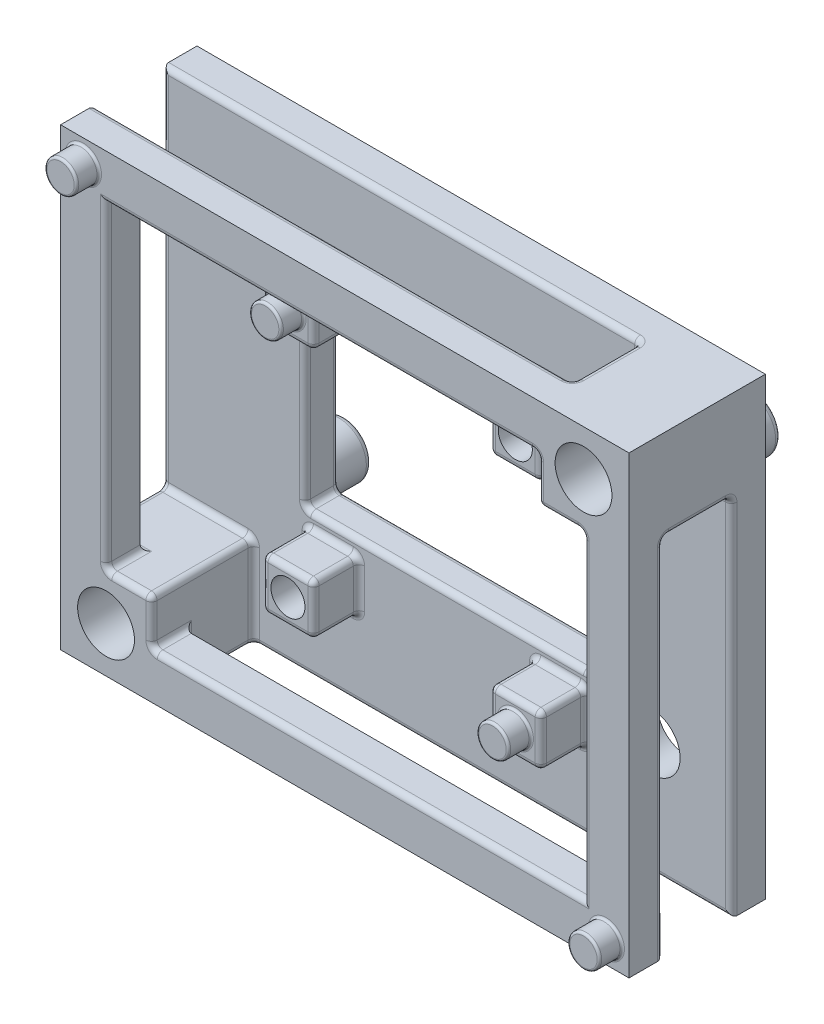
SolidWorks part; units mm, degrees
ref_plane "Ebene vorne" through (0, 0, 0) normal (0, 0, 1) x (1, 0, 0)
ref_plane "Ebene oben" through (0, 0, 0) normal (0, 1, 0) x (1, 0, 0)
ref_plane "Ebene rechts" through (0, 0, 0) normal (1, 0, 0) x (0, 0, -1)
sketch "Sketch1" plane through (0, 0, 0) normal (0, 0, 1) x (1, 0, 0)
  line L1 (-25, -20) -> (25, -20)
  line L2 (-25, -20) -> (-25, 20)
  line L3 (-25, 20) -> (25, 20)
  line L4 (25, -20) -> (25, 20)
  line L5 (-25, -20) -> (25, 20) construction
  line L6 (-25, 20) -> (25, -20) construction
  point P0 (0, 0)
  dimension "D1" = 50
  dimension "D2" = 40
extrude "Boss-Extrude1" add sketch "Sketch1" along normal blind 3 contours L2 L1 L4 L3
sketch "Sketch2" plane through (0, 0, 0) normal (0, 0, 1) x (1, 0, 0)
  line L2 (0, 0) -> (5.3997, -5.3997) construction
  circle A0 centre (18, 10) radius 2.4
  circle A2 centre (-18, -10) radius 2.4
  circle A4 centre (-18, -10) radius 2.4
  dimension "D3" = 4.8
  dimension "D6" = 4.8
  dimension "D1" = 18
  dimension "D2" = 10
  dimension "D4" = 18
  dimension "D5" = 10
extrude "Boss-Extrude2" add sketch "Sketch2" against normal blind 7 from offset 1 contours A0 | A2
sketch "Sketch3" plane through (0, 0, 0) normal (0, 0, 1) x (1, 0, 0)
  line L1 (-12, -7.5) -> (12, -7.5)
  line L2 (-12.5, -7) -> (-12.5, 7)
  line L3 (-12, 7.5) -> (12, 7.5)
  line L4 (12.5, -7) -> (12.5, 7)
  line L5 (-12.5, -7.5) -> (12.5, 7.5) construction
  line L6 (-12.5, 7.5) -> (12.5, -7.5) construction
  circle A0 centre (18, -10) radius 2.5
  circle A2 centre (-18, 10) radius 2.5
  circle A4 centre (-18, 10) radius 2.5
  arc A5 (-12.5, 7) -> (-12, 7.5) centre (-12, 7) cw
  arc A6 (12, -7.5) -> (12.5, -7) centre (12, -7) ccw
  arc A7 (-12, -7.5) -> (-12.5, -7) centre (-12, -7) cw
  arc A8 (12, 7.5) -> (12.5, 7) centre (12, 7) cw
  point P2 (0, 0)
  dimension "D3" = 5
  dimension "D6" = 5
  dimension "D9" = 0.5
  dimension "D1" = 18
  dimension "D2" = 10
  dimension "D4" = 10
  dimension "D5" = 18
  dimension "D7" = 25
  dimension "D8" = 15
extrude "Cut-Extrude1" cut sketch "Sketch3" along normal blind 15 contours A2 | A0 | A7 L1 A6 L4 A8 L3 A5 L2
fillet "Fillet1" radius 0.5 2 edges at (20.4, 10, -6) (-15.6, -10, -6)
sketch "Sketch12" plane through (0, 0, 0) normal (0, 0, 1) x (1, 0, 0)
  line L0 (0, 0) -> (0, -6.125) construction
  line L1 (-12.25, 13.25) -> (-7.75, 13.25)
  line L2 (-12.25, 13.25) -> (-12.25, 8.75)
  line L3 (-12.25, 8.75) -> (-7.75, 8.75)
  line L4 (-7.75, 13.25) -> (-7.75, 8.75)
  line L5 (-12.25, 13.25) -> (-7.75, 8.75) construction
  line L6 (-12.25, 8.75) -> (-7.75, 13.25) construction
  line L7 (0, 0) -> (9.2744, 0) construction
  line L8 (-12.25, -8.75) -> (-7.75, -13.25) construction
  line L9 (-12.25, -13.25) -> (-7.75, -8.75) construction
  line L10 (-7.75, -13.25) -> (-7.75, -8.75)
  line L11 (-12.25, -8.75) -> (-7.75, -8.75)
  line L12 (-12.25, -13.25) -> (-12.25, -8.75)
  line L13 (-12.25, -13.25) -> (-7.75, -13.25)
  line L14 (12.25, -13.25) -> (7.75, -8.75) construction
  line L15 (12.25, -8.75) -> (7.75, -13.25) construction
  line L16 (12.25, 8.75) -> (7.75, 13.25) construction
  line L17 (12.25, 13.25) -> (7.75, 8.75) construction
  line L18 (12.25, -13.25) -> (7.75, -13.25)
  line L19 (12.25, -13.25) -> (12.25, -8.75)
  line L20 (12.25, -8.75) -> (7.75, -8.75)
  line L21 (7.75, -13.25) -> (7.75, -8.75)
  line L22 (7.75, 13.25) -> (7.75, 8.75)
  line L23 (12.25, 8.75) -> (7.75, 8.75)
  line L24 (12.25, 13.25) -> (12.25, 8.75)
  line L25 (12.25, 13.25) -> (7.75, 13.25)
  circle A0 centre (-10, 11) radius 1.5
  circle A1 centre (-10, -11) radius 1.5
  circle A2 centre (10, -11) radius 1.5
  circle A3 centre (10, 11) radius 1.5
  point P0 (-10, 11)
  dimension "D5" = 3
  dimension "D1" = 10
  dimension "D2" = 11
  dimension "D3" = 4.5
  dimension "D4" = 4.5
extrude "Boss-Extrude3" add sketch "Sketch12" along normal blind 7
sketch "Sketch13" plane through (0, 0, 0) normal (0, 0, 1) x (1, 0, 0)
  line L0 (0, 0) -> (-6.7923, 0) construction
  line L1 (17, 20) -> (25, 20)
  line L2 (17, 20) -> (17, 12)
  line L3 (17, 12) -> (25, 12)
  line L4 (25, 20) -> (25, 12)
  line L5 (17, 20) -> (25, 12) construction
  line L6 (17, 12) -> (25, 20) construction
  line L7 (0, 0) -> (0, 5.1433) construction
  line L9 (-25, -12) -> (-17, -12)
  line L10 (-25, -12) -> (-25, -20)
  line L11 (-25, -20) -> (-17, -20)
  line L12 (-17, -12) -> (-17, -20)
  line L13 (-25, -12) -> (-17, -20) construction
  line L14 (-25, -20) -> (-17, -12) construction
  circle A0 centre (21, 16) radius 2.5
  circle A1 centre (-21, -16) radius 2.5
  point P0 (21, 16)
  point P11 (-21, -16)
  dimension "D5" = 5
  dimension "D10" = 5
  dimension "D1" = 21
  dimension "D2" = 16
  dimension "D3" = 8
  dimension "D4" = 8
  dimension "D6" = 16
  dimension "D7" = 21
  dimension "D8" = 8
  dimension "D9" = 8
extrude "Boss-Extrude4" add sketch "Sketch13" along normal blind 12
sketch "Sketch14" plane through (0, 0, 0) normal (0, 0, 1) x (1, 0, 0)
  line L1 (-25, -20) -> (25, -20)
  line L2 (-25, -20) -> (-25, 20)
  line L3 (-25, 20) -> (25, 20)
  line L4 (25, -20) -> (25, 20)
  line L5 (-25, -20) -> (25, 20) construction
  line L6 (-25, 20) -> (25, -20) construction
  line L7 (-21, -16) -> (21, -16)
  line L8 (-21, -16) -> (-21, 16)
  line L9 (-21, 16) -> (21, 16)
  line L10 (21, -16) -> (21, 16)
  line L11 (-21, -16) -> (21, 16) construction
  line L12 (-21, 16) -> (21, -16) construction
  point P0 (0, 0)
  point P6 (0, 0)
  dimension "D1" = 40
  dimension "D2" = 50
  dimension "D3" = 32
  dimension "D4" = 42
extrude "Boss-Extrude5" add sketch "Sketch14" along normal blind 3 from offset 9
sketch "Sketch15" plane through (0, 0, 0) normal (0, 0, 1) x (1, 0, 0)
  circle A0 centre (-10, 11) radius 2
  circle A1 centre (10, -11) radius 2
  dimension "D1" = 4
  dimension "D2" = 4
extrude "Boss-Extrude6" add sketch "Sketch15" along normal blind 7
sketch "Sketch16" plane through (0, 0, 0) normal (0, 0, 1) x (1, 0, 0)
  circle A0 centre (-10, 11) radius 1.4
  circle A1 centre (10, -11) radius 1.4
  dimension "D3" = 2.8
  dimension "D4" = 2.8
  dimension "D1" = 11
  dimension "D2" = 10
  dimension "D5" = 11
  dimension "D6" = 10
extrude "Boss-Extrude7" add sketch "Sketch16" along normal blind 9
sketch "Sketch17" plane through (0, 0, 0) normal (0, 0, 1) x (1, 0, 0)
  circle A0 centre (-21, -16) radius 2.5
  circle A1 centre (21, 16) radius 2.5
  circle A2 centre (10, 11) radius 1.5
  circle A3 centre (-10, -11) radius 1.5
  dimension "D1" = 3
  dimension "D2" = 3
  dimension "D3" = 5
  dimension "D4" = 5
  dimension "D5" = 21
  dimension "D6" = 16
extrude "Cut-Extrude2" cut sketch "Sketch17" along normal blind 15 from offset 1 offset against normal yes
fillet "Fillet4" radius 0.5 50 edges at (-25, 4, 3) (-21, 2, 12) (-25, 4, 9) (2, -16, 12) (4, -20, 3) (4, -20, 9) (-2, 16, 12) (-4, 20, 3) (-4, 20, 9) (25, -4, 3) (21, -2, 12) (25, -4, 9) (-12.3536, 7.3536, 0) (-12.5, 0, 0) (-12.3536, -7.3536, 0) (0, -7.5, 0) (12.3536, -7.3536, 0) (12.5, 0, 0) (12.3536, 7.3536, 0) (12.3536, 7.3536, 3) (12.5, 0, 3) (12.3536, -7.3536, 3) (0, -7.5, 3) (-12.3536, -7.3536, 3) (-12.5, 0, 3) (-12.3536, 7.3536, 3) (-21, -12, 3) (-19, -12, 12) (-21, -12, 10.5) (-23, -12, 9) (-25, -12, 6) (-17, -14, 12) (-17, -12, 7.5) (-17, -16, 3) (-17, -20, 6) (-17, -18, 9) (-17, -16, 10.5) (17, 14, 12) (17, 16, 3) (17, 20, 6) (17, 18, 9) (17, 16, 10.5) (21, 12, 3) (17, 12, 7.5) (19, 12, 12) (21, 12, 10.5) (23, 12, 9) (25, 12, 6) (0, 7.5, 0) (0, 7.5, 3)
fillet "Fillet5" radius 0.5 48 edges at (-7.75, -11, 3) (-10, -8.75, 3) (-10, -13.25, 7) (-7.75, -13.25, 5) (-10, -13.25, 3) (-12.25, -8.75, 5) (-12.25, -11, 7) (-12.25, -13.25, 5) (-12.25, -11, 3) (-7.75, -8.75, 5) (12.25, 11, 7) (12.25, 11, 3) (12.25, -11, 3) (12.25, -11, 7) (12.25, -8.75, 5) (10, -8.75, 3) (10, -8.75, 7) (12.25, 13.25, 5) (10, 13.25, 7) (10, 13.25, 3) (7.75, -8.75, 5) (7.75, -11, 3) (7.75, -11, 7) (7.75, 13.25, 5) (7.75, 11, 7) (7.75, 11, 3) (7.75, -13.25, 5) (10, -13.25, 3) (10, -13.25, 7) (12.25, -13.25, 5) (7.75, 8.75, 5) (10, 8.75, 7) (12.25, 8.75, 5) (10, 8.75, 3) (-12.25, 11, 3) (-12.25, 11, 7) (-10, 13.25, 3) (-10, 13.25, 7) (-12.25, 13.25, 5) (-12.25, 8.75, 5) (-10, 8.75, 3) (-10, 8.75, 7) (-7.75, 8.75, 5) (-7.75, 11, 3) (-7.75, 11, 7) (-7.75, 13.25, 5) (-10, -8.75, 7) (-7.75, -11, 7)
fillet "Fillet6" radius 0.2 2 edges at (11.4, -11, 9) (-8.6, 11, 9)
fillet "Fillet7" radius 0.2 2 edges at (11.4, -11, 7) (-8.6, 11, 7)
sketch "Sketch18" plane through (0, 0, 0) normal (0, 0, 1) x (1, 0, 0)
  circle A0 centre (-23, 18) radius 1.4
  circle A1 centre (23, -18) radius 1.4
  dimension "D3" = 2.8
  dimension "D6" = 2.8
  dimension "D1" = 18
  dimension "D2" = 23
  dimension "D4" = 18
  dimension "D5" = 23
extrude "Boss-Extrude8" add sketch "Sketch18" along normal blind 3 from offset 11
fillet "Fillet8" radius 0.2 4 edges at (24.4, -18, 14) (24.4, -18, 12) (-21.6, 18, 14) (-21.6, 18, 12)
fillet "Fillet9" radius 0.2 2 edges at (-15.6, -10, 0) (20.4, 10, 0)
